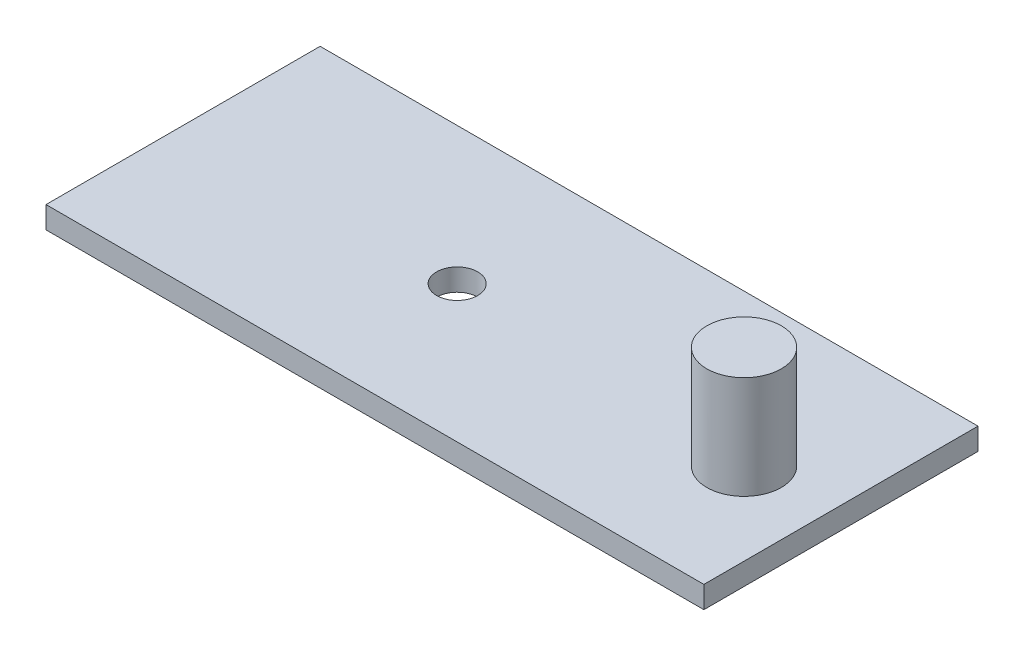
SolidWorks part; units mm, degrees
ref_plane "Front Plane" through (0, 0, 0) normal (0, 0, 1) x (1, 0, 0)
ref_plane "Top Plane" through (0, 0, 0) normal (0, 1, 0) x (1, 0, 0)
ref_plane "Right Plane" through (0, 0, 0) normal (1, 0, 0) x (0, 0, -1)
sketch "Sketch1" plane through (0, 0, 0) normal (0, 1, 0) x (1, 0, 0)
  line L1 (0, 0) -> (48, 0)
  line L2 (0, 0) -> (0, 20)
  line L3 (0, 20) -> (48, 20)
  line L4 (48, 0) -> (48, 20)
  circle A0 centre (20, 10) radius 1.5
  circle A1 centre (38, 13.5) radius 1.5
  point P9 (41.1916, 13.7625)
  dimension "D3" = 3
  dimension "D1" = 48
  dimension "D2" = 20
  dimension "D4" = 20
  dimension "D5" = 10
  dimension "D6" = 13.5
  dimension "D7" = 10
extrude "Boss-Extrude1" add sketch "Sketch1" along normal blind 1.6
sketch "Sketch2" plane through (0, 1.6, 0) normal (0, 1, 0) x (1, 0, 0)
  circle A0 centre (41.9848, 8.9471) radius 2.7192
extrude "Boss-Extrude2" add sketch "Sketch2" along normal blind 7.5
